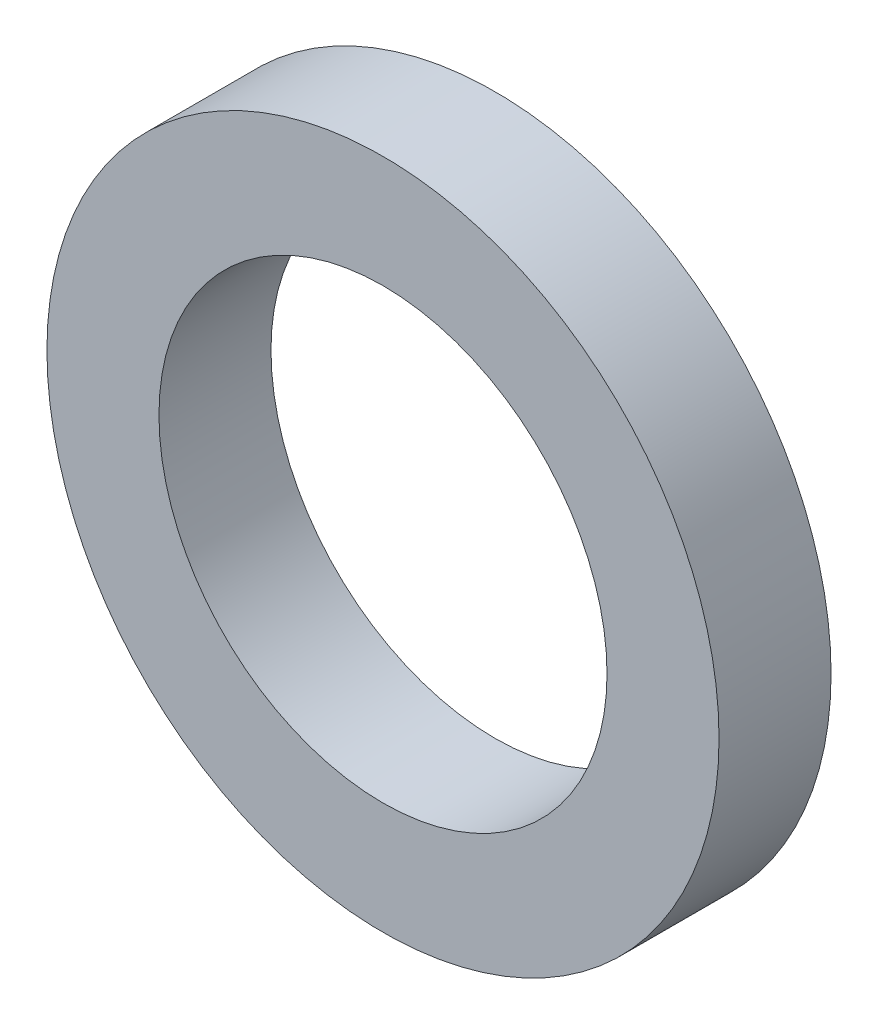
SolidWorks part; units mm, degrees
ref_plane "Front" through (0, 0, 0) normal (0, 0, 1) x (1, 0, 0)
ref_plane "Top" through (0, 0, 0) normal (0, 1, 0) x (1, 0, 0)
ref_plane "Right" through (0, 0, 0) normal (1, 0, 0) x (0, 0, -1)
sketch "Sketch1" plane through (0, 0, 0) normal (0, 1, 0) x (1, 0, 0)
  line L0 (0, -0.635) -> (0, 0.635) construction
  line L1 (0, -0.55) -> (0, 0.55) construction
  line L3 (-2, 0) -> (2, 0) construction
  line L4 (2, -0.365) -> (2, 0.635)
  line L5 (2, -0.365) -> (3, -0.365)
  line L6 (2, 0.635) -> (3, 0.635)
  line L7 (3, -0.365) -> (3, 0.635)
  point P9 (2, 0)
  point P10 (1.8034, 0)
  point P13 (1.1684, 0.635)
  point P14 (1.1684, -0.635)
  dimension "D1" = 1
  dimension "Width" = 1
revolve "Revolve1" add sketch "Sketch1" angle 360 about L0
sketch "Sketch3" plane through (0, 0, 0) normal (1, 0, 0) x (0, 0, -1)
  line L0 (-0.5, 0) -> (0.5, 0) construction
  point P6 (0, 0)
  point P7 (0, 0)
  dimension "D1" = 1
sketch "Sketch4" plane through (0, 0, 0) normal (0, 0, 1) x (1, 0, 0)
  line L1 (0, 0) -> (-2.9322, 0.6341) construction
  circle A0 centre (0, 0) radius 3 construction
equation "\"D1@Sketch3\" = \"Width@Sketch1\""
equation "\"D1@Sketch1\" = \"Width@Sketch1\""
